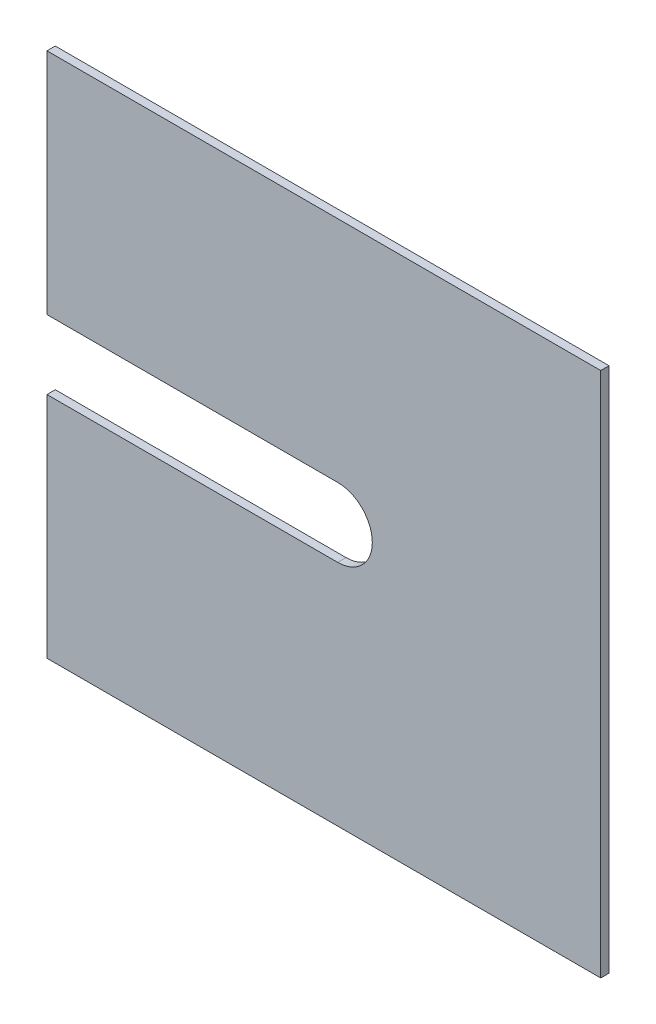
SolidWorks part; units mm, degrees
ref_plane "Alzado" through (0, 0, 0) normal (0, 0, 1) x (1, 0, 0)
ref_plane "Planta" through (0, 0, 0) normal (0, 1, 0) x (1, 0, 0)
ref_plane "Vista lateral" through (0, 0, 0) normal (1, 0, 0) x (0, 0, -1)
sketch "Croquis1" plane through (0, 0, 0) normal (0, 0, 1) x (1, 0, 0)
  line L1 (-100, -95) -> (100, -95)
  line L2 (-100, -95) -> (-100, 95)
  line L3 (-100, 95) -> (100, 95)
  line L4 (100, -95) -> (100, 95)
  line L5 (-100, -95) -> (100, 95) construction
  line L6 (-100, 95) -> (100, -95) construction
  point P0 (0, 0)
  dimension "D1" = 190
  dimension "D2" = 200
extrude "Saliente-Extruir1" add sketch "Croquis1" along normal blind 3
sketch "Croquis2" plane through (0, 0, 3) normal (0, 0, 1) x (1, 0, 0)
  line L0 (100, 0) -> (17.5, 0) construction
  line L1 (100, -95) -> (100, 95) construction
  line L2 (5, 12.5) -> (-100, 12.5)
  line L3 (-100, 95) -> (-100, -95) construction
  line L4 (-100, 12.5) -> (-100, 0)
  line L5 (-100, 0) -> (-100, -12.5)
  line L6 (-100, -12.5) -> (5, -12.5)
  arc A0 (5, -12.5) -> (5, 12.5) centre (5, 0) ccw
  dimension "D2" = 25
  dimension "D1" = 95
extrude "Cortar-Extruir1" cut sketch "Croquis2" against normal blind 3
